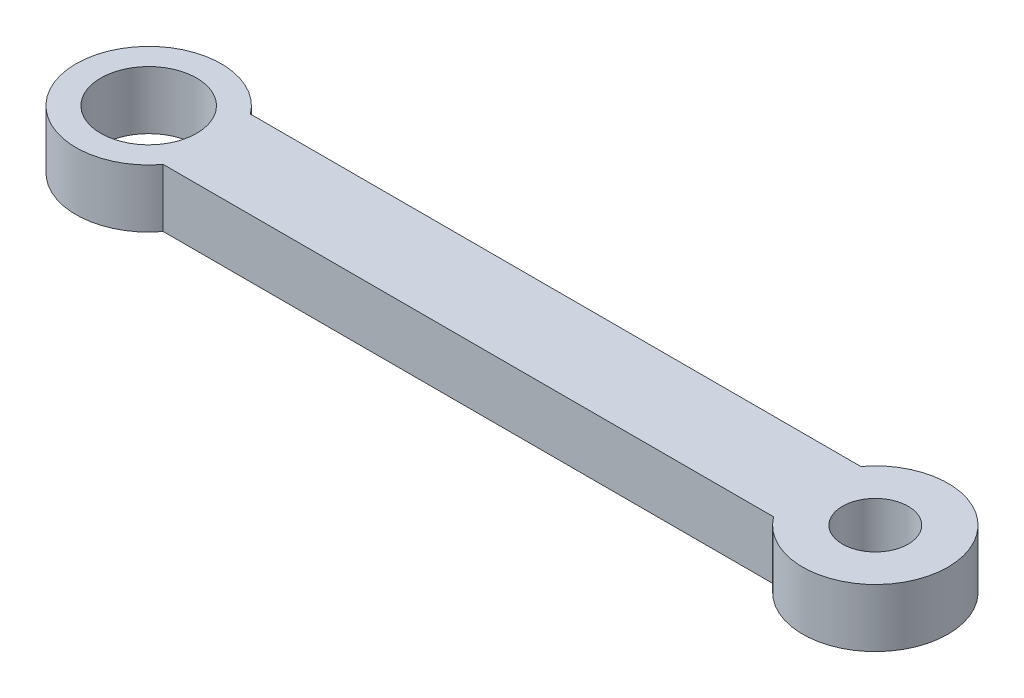
SolidWorks part; units mm, degrees
ref_plane "Front Plane" through (0, 0, 0) normal (0, 0, 1) x (1, 0, 0)
ref_plane "Top Plane" through (0, 0, 0) normal (0, 1, 0) x (1, 0, 0)
ref_plane "Right Plane" through (0, 0, 0) normal (1, 0, 0) x (0, 0, -1)
sketch "Sketch1" plane through (0, 0, 0) normal (0, 1, 0) x (1, 0, 0)
  line L0 (-10.5, 1.5) -> (10.5, 1.5)
  line L1 (-12.5, -1.5) -> (12.5, -1.5) construction
  line L2 (-12.5, -1.5) -> (-12.5, 1.5) construction
  line L3 (-12.5, 1.5) -> (12.5, 1.5) construction
  line L4 (12.5, -1.5) -> (12.5, 1.5) construction
  line L5 (-12.5, -1.5) -> (12.5, 1.5) construction
  line L6 (-12.5, 1.5) -> (12.5, -1.5) construction
  line L7 (-10.5, -1.5) -> (10.5, -1.5)
  circle A0 centre (-12.5, 0) radius 2.5 construction
  circle A1 centre (12.5, 0) radius 2.5 construction
  arc A2 (-10.5, 1.5) -> (-10.5, -1.5) centre (-12.5, 0) ccw
  arc A3 (10.5, 1.5) -> (10.5, -1.5) centre (12.5, 0) cw
  circle A4 centre (-12.5, 0) radius 1.65
  circle A5 centre (12.5, 0) radius 1.1303
  point P0 (0, 0)
  dimension "D3" = 5
  dimension "D4" = 3.3
  dimension "D5" = 2.2606
  dimension "D1" = 25
  dimension "D2" = 3
extrude "Boss-Extrude1" add sketch "Sketch1" along normal blind 2
